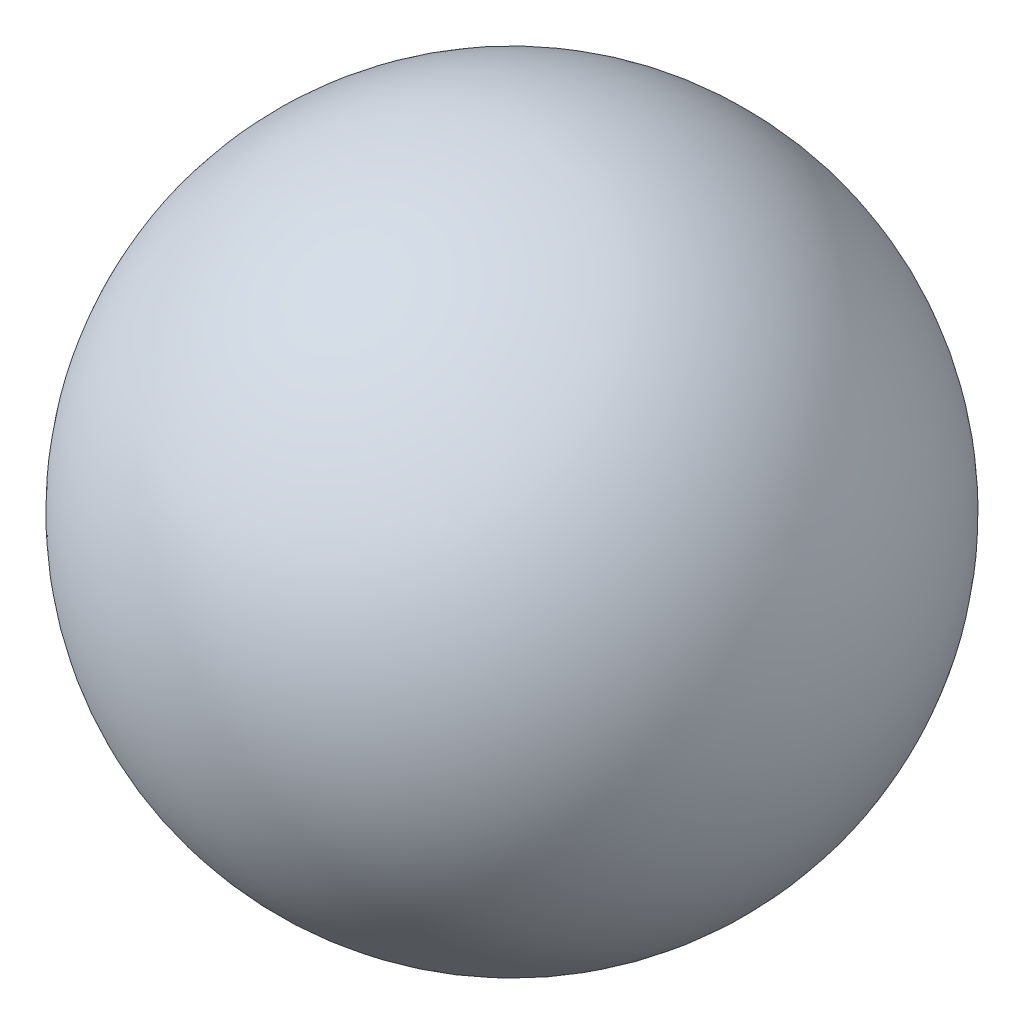
SolidWorks part; units mm, degrees
ref_plane "Front Plane" through (0, 0, 0) normal (0, 0, 1) x (1, 0, 0)
ref_plane "Top Plane" through (0, 0, 0) normal (0, 1, 0) x (1, 0, 0)
ref_plane "Right Plane" through (0, 0, 0) normal (1, 0, 0) x (0, 0, -1)
ref_plane "Plane1" through (0, 0, 0) normal (0, 0, 1) x (1, 0, 0)
sketch "Sketch1" plane through (0, 0, 0) normal (0, 0, 1) x (1, 0, 0)
  line L0 (3.6905, 4.75) -> (1.3095, 4.75)
  line L1 (3.6905, 4.75) -> (1.3095, 4.75) construction
  arc A0 (1.3095, 4.75) -> (3.6905, 4.75) centre (2.5, 4.75) cw
revolve "Revolve1" add sketch "Sketch1" angle 360 about L1
